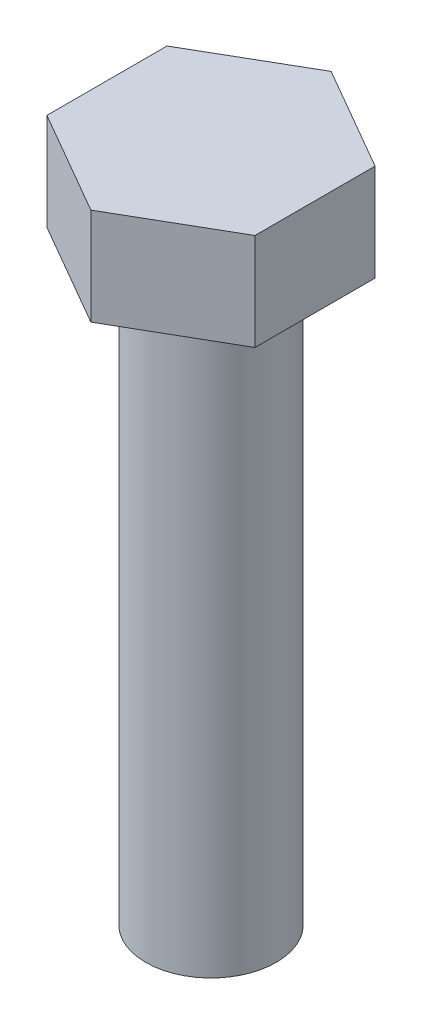
SolidWorks part; units mm, degrees
ref_plane "Front Plane" through (0, 0, 0) normal (0, 0, 1) x (1, 0, 0)
ref_plane "Top Plane" through (0, 0, 0) normal (0, 1, 0) x (1, 0, 0)
ref_plane "Right Plane" through (0, 0, 0) normal (1, 0, 0) x (0, 0, -1)
sketch "Sketch1" plane through (0, 0, 0) normal (0, 1, 0) x (1, 0, 0)
  line L1 (0, 6.2912) -> (-5.4483, 3.1456)
  line L2 (-5.4483, 3.1456) -> (-5.4483, -3.1456)
  line L3 (-5.4483, -3.1456) -> (0, -6.2912)
  line L4 (0, -6.2912) -> (5.4483, -3.1456)
  line L5 (5.4483, -3.1456) -> (5.4483, 3.1456)
  line L6 (5.4483, 3.1456) -> (0, 6.2912)
  circle A0 centre (0, 0) radius 5.4483 construction
  dimension "D1" = 10.8966
extrude "Boss-Extrude1" add sketch "Sketch1" along normal blind 5.08
sketch "Sketch2" plane through (0, 0, 0) normal (0, -1, 0) x (1, 0, 0)
  circle A0 centre (0, 0) radius 3.4163
  dimension "D1" = 6.8326
extrude "Boss-Extrude2" add sketch "Sketch2" along normal blind 30.48
